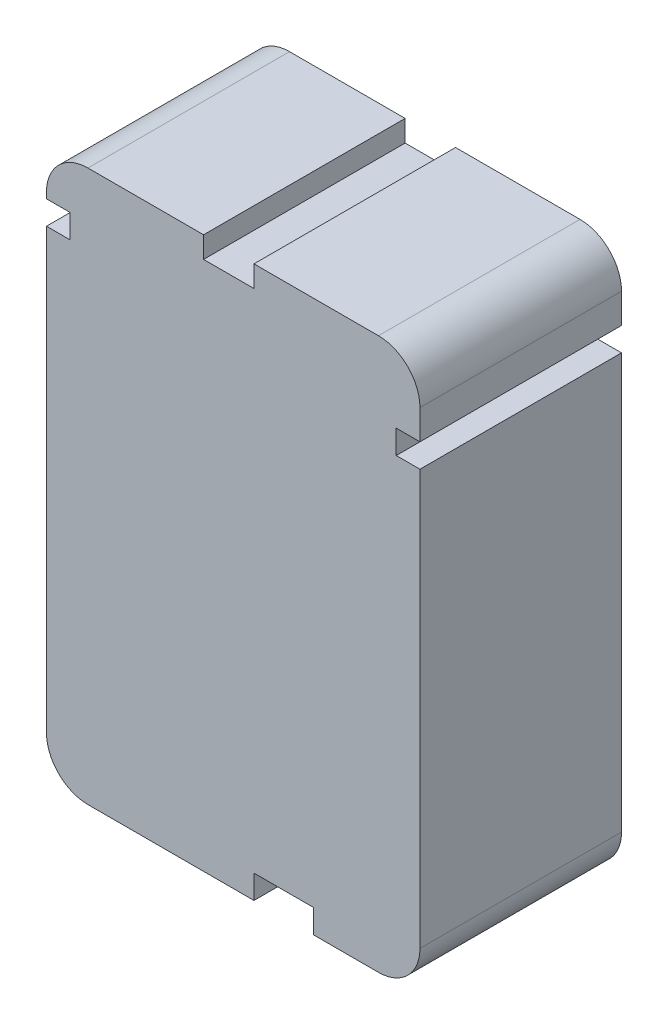
SolidWorks part; units mm, degrees
ref_plane "Piano frontale" through (0, 0, 0) normal (0, 0, 1) x (1, 0, 0)
ref_plane "Piano superiore" through (0, 0, 0) normal (0, 1, 0) x (1, 0, 0)
ref_plane "Piano destro" through (0, 0, 0) normal (1, 0, 0) x (0, 0, -1)
sketch "Schizzo1" plane through (0, 0, 0) normal (0, 0, 1) x (1, 0, 0)
  line L0 (-16.9408, 170.0533) -> (-21.3988, 120.2524) construction
  line L1 (0, 42.5) -> (2, 42.5)
  line L2 (3.5, 0) -> (28, 0)
  line L3 (0, 3.5) -> (0, 43)
  line L4 (3.5, 46.5) -> (28, 46.5)
  line L5 (31.5, 3.5) -> (31.5, 43)
  line L6 (2, 42.5) -> (2, 40.5)
  line L7 (2, 40.5) -> (0, 40.5)
  line L8 (31.5, 40.5) -> (29.5, 40.5)
  line L9 (29.5, 40.5) -> (29.5, 38.5)
  line L10 (29.5, 38.5) -> (31.5, 38.5)
  line L11 (17.5, 0) -> (17.5, 2)
  line L12 (17.5, 2) -> (22.5, 2)
  line L13 (22.5, 2) -> (22.5, 0)
  line L14 (13.25, 46.5) -> (13.25, 44.6986)
  line L15 (13.25, 44.6986) -> (17.5, 44.6986)
  line L16 (17.5, 44.6986) -> (17.5, 46.5)
  arc A0 (0, 43) -> (3.5, 46.5) centre (3.5, 43) cw
  arc A1 (28, 46.5) -> (31.5, 43) centre (28, 43) cw
  arc A2 (28, 0) -> (31.5, 3.5) centre (28, 3.5) ccw
  arc A3 (3.5, 0) -> (0, 3.5) centre (3.5, 3.5) cw
  point P25 (0, 46.5)
  point P28 (31.5, 46.5)
  point P31 (31.5, 0)
  point P34 (0, 0)
  dimension "D15" = 3.5
  dimension "D1" = 50
  dimension "D2" = 31.5
  dimension "D3" = 2
  dimension "D4" = 2
  dimension "D5" = 46.5
  dimension "D6" = 4
  dimension "D7" = 2
  dimension "D8" = 2
  dimension "D9" = 6
  dimension "D10" = 5
  dimension "D11" = 2
  dimension "D12" = 9
  dimension "D13" = 4.25
  dimension "D14" = 13.25
extrude "Estrusione-Estrusione2" add sketch "Schizzo1" along normal blind 17 contours A3 L2 L11 L12 L13 A2 L5 L10 L9 L8 A1 L4 L16 L15 L14 A0 L3 L1 L6 L7
sketch "Schizzo2" plane through (0, 0, 0) normal (0, 0, -1) x (-1, 0, 0)
  line L0 (-17.0012, 46.5) -> (-17.0012, 0) construction
  line L1 (-17.5, 46.5) -> (-28, 46.5) construction
  line L3 (-3.5, 0) -> (-17.5, 0) construction
  text T0 "<b>SOPRA</b>"
  point P4 (-17.0637, 0.4158)
  point P5 (-17.0012, 0)
  point P7 (-17.0012, 2)
extrude "Taglio-Estrusione1" cut sketch "Schizzo2" against normal blind 0.5
